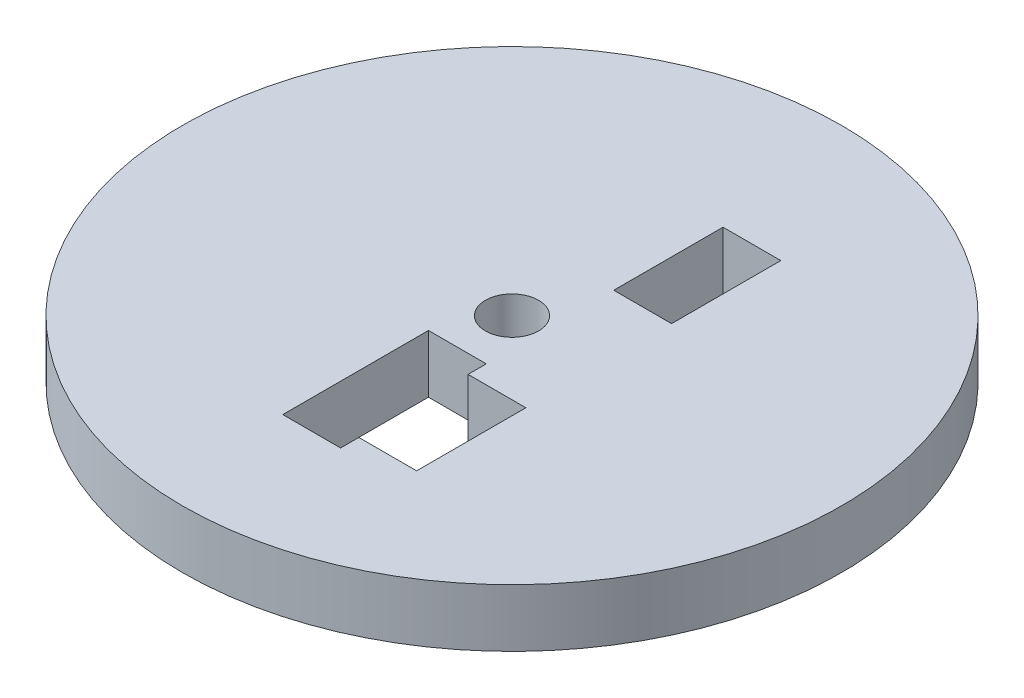
SolidWorks part; units mm, degrees
ref_plane "Front Plane" through (0, 0, 0) normal (0, 0, 1) x (1, 0, 0)
ref_plane "Top Plane" through (0, 0, 0) normal (0, 1, 0) x (1, 0, 0)
ref_plane "Right Plane" through (0, 0, 0) normal (1, 0, 0) x (0, 0, -1)
sketch "Sketch1" plane through (0, 0, 0) normal (0, 1, 0) x (1, 0, 0)
  line L4 (1.5875, -4) -> (1.5875, -3)
  line L5 (1.5875, 4) -> (4.7625, 4)
  line L6 (1.5875, 4) -> (1.5875, 10)
  line L7 (1.5875, 10) -> (4.7625, 10)
  line L8 (4.7625, 4) -> (4.7625, 10)
  line L9 (1.5875, -4) -> (4.7625, -4)
  line L11 (1.5875, -10) -> (4.7625, -10)
  line L12 (4.7625, -4) -> (4.7625, -10)
  line L13 (-1.5875, -3) -> (1.5875, -3)
  line L14 (-1.5875, -3) -> (-1.5875, -11)
  line L15 (-1.5875, -11) -> (1.5875, -11)
  line L17 (1.5875, -11) -> (1.5875, -10)
  circle A1 centre (0, 0) radius 1.4605
  circle A2 centre (0, 0) radius 18.0975
  point P14 (0, -3)
  dimension "D1" = 36.195
  dimension "D4" = 2.921
  dimension "D2" = 3.175
  dimension "D3" = 6
  dimension "D5" = 20
  dimension "D6" = 4
  dimension "D7" = 3.175
  dimension "D8" = 8
  dimension "D9" = 1
extrude "Boss-Extrude1" add sketch "Sketch1" along normal blind 3.175
